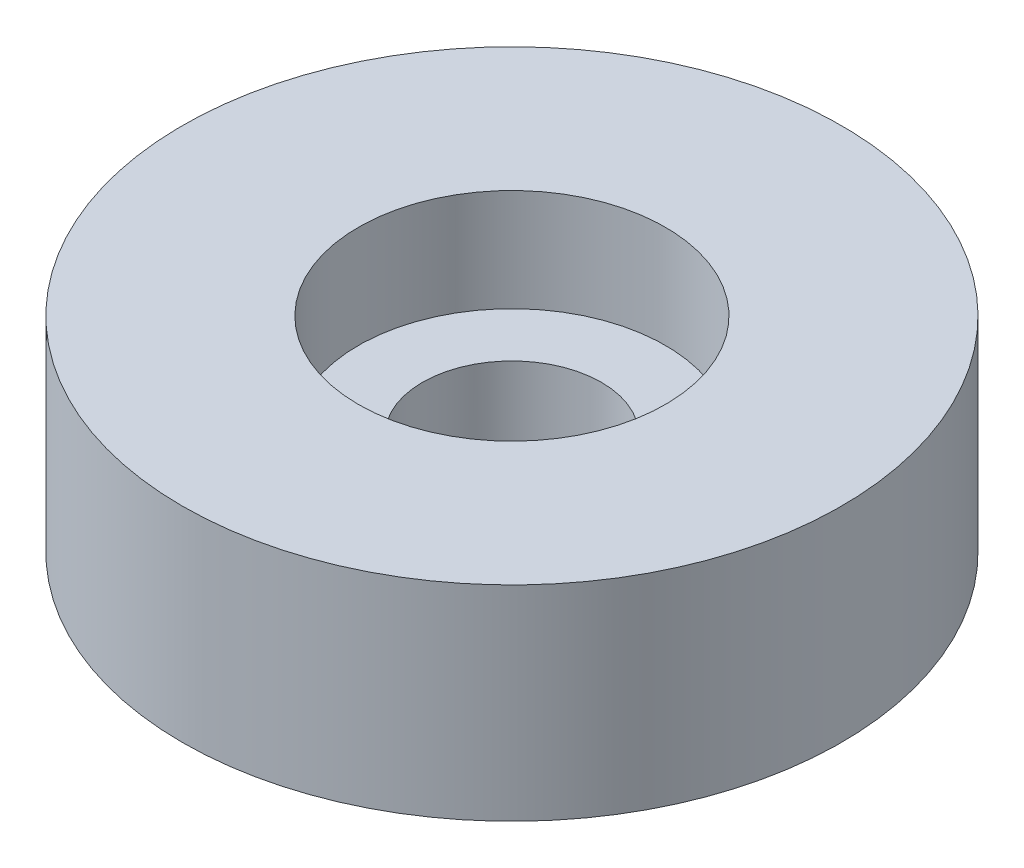
SolidWorks part; units mm, degrees
material "ABS"
ref_plane "Front Plane" through (0, 0, 0) normal (0, 0, 1) x (1, 0, 0)
ref_plane "Top Plane" through (0, 0, 0) normal (0, 1, 0) x (1, 0, 0)
ref_plane "Right Plane" through (0, 0, 0) normal (1, 0, 0) x (0, 0, -1)
sketch "Sketch1" plane through (0, 0, 0) normal (0, 1, 0) x (1, 0, 0)
  circle A0 centre (0, 0) radius 1.75
  circle A1 centre (0, 0) radius 6.44
  dimension "D1" = 3.5
  dimension "D2" = 12.88
extrude "Boss-Extrude1" add sketch "Sketch1" along normal blind 4
sketch "Sketch2" plane through (0, 4, 0) normal (0, 1, 0) x (1, 0, 0)
  circle A0 centre (0, 0) radius 3
  dimension "D1" = 6
extrude "Cut-Extrude1" cut sketch "Sketch2" against normal blind 2
sketch "Sketch3" plane through (0, 0, 0) normal (0, -1, 0) x (1, 0, 0)
  circle A0 centre (0, 0) radius 1.75
  circle A1 centre (0, 0) radius 2.5
  dimension "D1" = 5
extrude "Boss-Extrude2" add sketch "Sketch3" along normal blind 0.5
